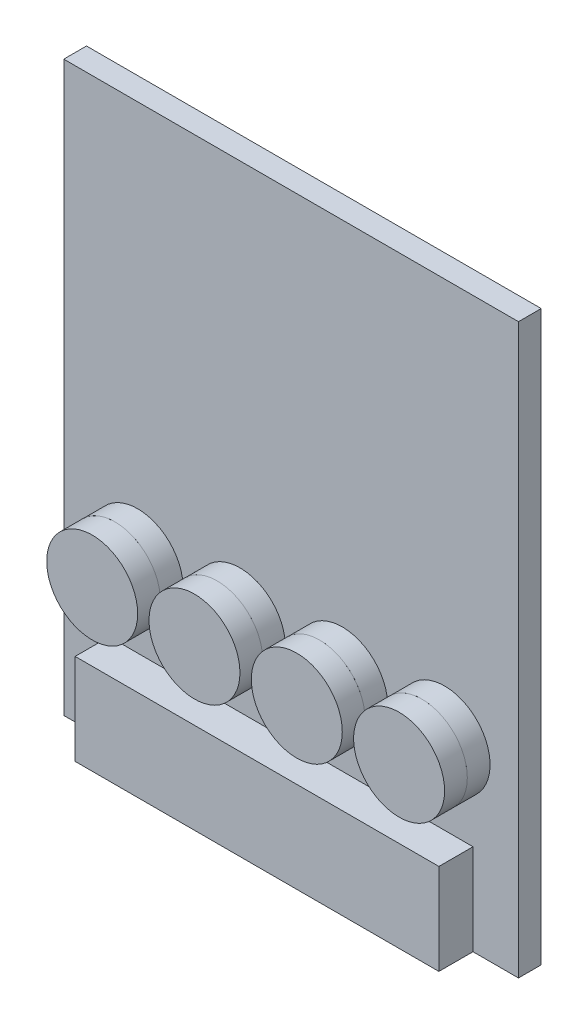
SolidWorks part; units mm, degrees
ref_plane "前视基准面" through (0, 0, 0) normal (0, 0, 1) x (1, 0, 0)
ref_plane "上视基准面" through (0, 0, 0) normal (0, 1, 0) x (1, 0, 0)
ref_plane "右视基准面" through (0, 0, 0) normal (1, 0, 0) x (0, 0, -1)
sketch "草图1" plane through (0, 0, 0) normal (0, 0, 1) x (1, 0, 0)
  line L1 (0, 0) -> (40, 0)
  line L2 (0, 0) -> (0, 50)
  line L3 (0, 50) -> (40, 50)
  line L4 (40, 0) -> (40, 50)
  dimension "D1" = 50
  dimension "D2" = 40
extrude "凸台-拉伸1" add sketch "草图1" along normal blind 2
sketch "草图2" plane through (0, 0, 2) normal (0, 0, 1) x (1, 0, 0)
  line L0 (0, 50) -> (0, 0) construction
  line L2 (0, 0) -> (40, 0) construction
  circle A0 centre (6.5, 15) radius 4
  circle A1 centre (15.5, 15) radius 4
  circle A2 centre (24.5, 15) radius 4
  circle A3 centre (33.5, 15) radius 4
  point P8 (0, 0)
  point P9 (0, 0)
  point P11 (20.5449, 16.247)
  dimension "D1" = 8
  dimension "D5" = 6.5
  dimension "D2" = 18
  dimension "D3" = 9
  dimension "D4" = 9
  dimension "D6" = 15
extrude "凸台-拉伸2" add sketch "草图2" along normal blind 2
sketch "草图3" plane through (0, 0, 4) normal (0, 0, 1) x (1, 0, 0)
  circle A0 centre (6.5, 15) radius 4
extrude "凸台-拉伸3" add sketch "草图3" along normal blind 2 separate body
sketch "草图4" plane through (0, 0, 4) normal (0, 0, 1) x (1, 0, 0)
  circle A0 centre (15.5, 15) radius 4
extrude "凸台-拉伸4" add sketch "草图4" along normal blind 2 separate body
sketch "草图5" plane through (0, 0, 4) normal (0, 0, 1) x (1, 0, 0)
  circle A0 centre (24.5, 15) radius 4
extrude "凸台-拉伸5" add sketch "草图5" along normal blind 2 separate body
sketch "草图7" plane through (0, 0, 4) normal (0, 0, 1) x (1, 0, 0)
  circle A0 centre (33.5, 15) radius 4
extrude "凸台-拉伸6" add sketch "草图7" along normal blind 2 separate body
sketch "草图8" plane through (0, 0, 2) normal (0, 0, 1) x (1, 0, 0)
  line L0 (0, 0) -> (40, 0) construction
  line L1 (4, 8) -> (36, 8)
  line L2 (4, 8) -> (4, 0)
  line L3 (4, 0) -> (36, 0)
  line L4 (36, 8) -> (36, 0)
  line L5 (40, 0) -> (40, 50) construction
  dimension "D1" = 32
  dimension "D2" = 8
  dimension "D3" = 4
extrude "凸台-拉伸7" add sketch "草图8" along normal blind 3
